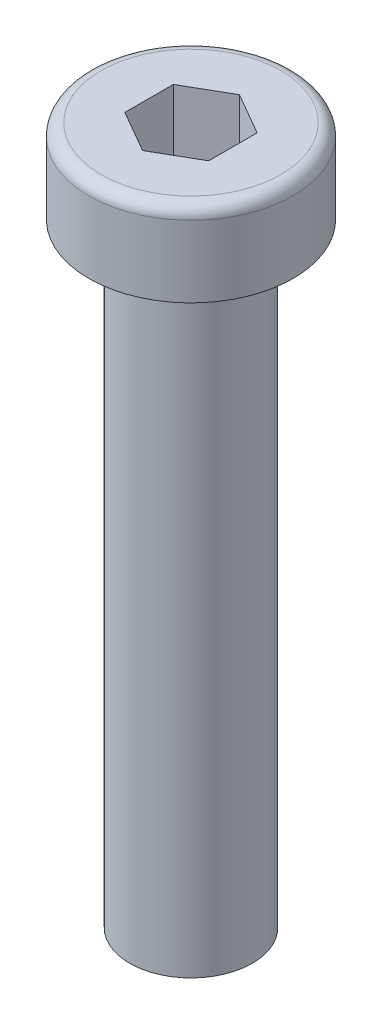
SolidWorks part; units mm, degrees
ref_plane "Front Plane" through (0, 0, 0) normal (0, 0, 1) x (1, 0, 0)
ref_plane "Top Plane" through (0, 0, 0) normal (0, 1, 0) x (1, 0, 0)
ref_plane "Right Plane" through (0, 0, 0) normal (1, 0, 0) x (0, 0, -1)
sketch "Sketch1" plane through (0, 0, 0) normal (0, 1, 0) x (1, 0, 0)
  circle A0 centre (0, 0) radius 5
  dimension "D1" = 10
extrude "Boss-Extrude1" add sketch "Sketch1" along normal blind 4.1
fillet "Fillet1" radius 0.6 1 edges at (0, 4.1, 5)
sketch "Sketch2" plane through (0, 4.1, 0) normal (0, 1, 0) x (1, 0, 0)
  line L1 (0, -2.3671) -> (2.05, -1.1836)
  line L2 (2.05, -1.1836) -> (2.05, 1.1836)
  line L3 (2.05, 1.1836) -> (0, 2.3671)
  line L4 (0, 2.3671) -> (-2.05, 1.1836)
  line L5 (-2.05, 1.1836) -> (-2.05, -1.1836)
  line L6 (-2.05, -1.1836) -> (0, -2.3671)
  circle A0 centre (0, 0) radius 2.05 construction
  dimension "D1" = 4.1
extrude "Cut-Extrude1" cut sketch "Sketch2" against normal blind 3.6
sketch "Sketch3" plane through (0, 0, 0) normal (0, -1, 0) x (1, 0, 0)
  circle A0 centre (0, 0) radius 3
  dimension "D1" = 6
extrude "Boss-Extrude2" add sketch "Sketch3" along normal blind 30
